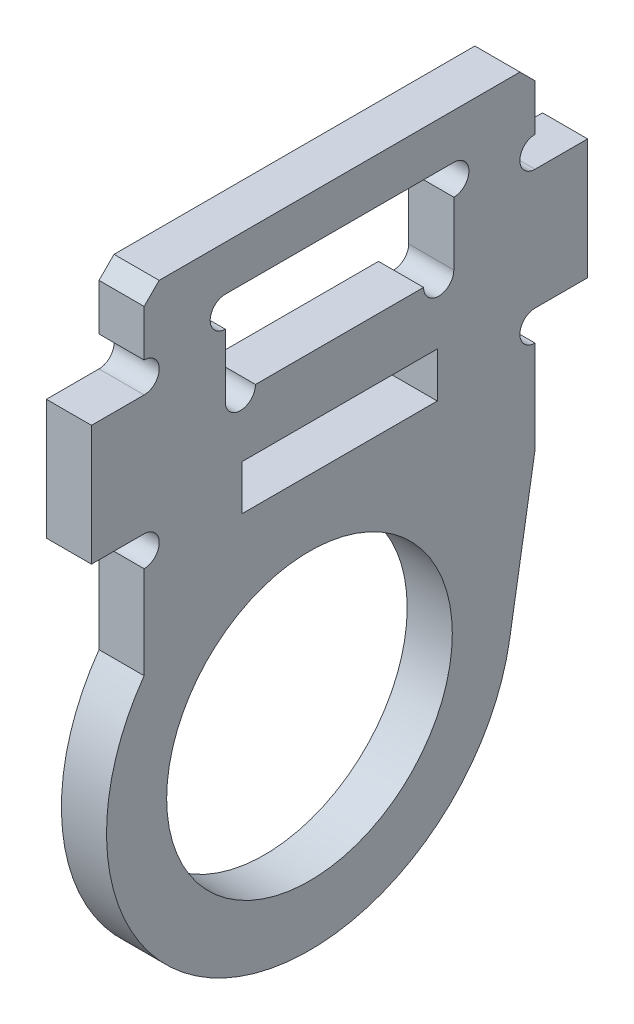
SolidWorks part; units mm, degrees
material "Thornel Mat VMA"
ref_plane "前视基准面" through (0, 0, 0) normal (0, 0, 1) x (1, 0, 0)
ref_plane "上视基准面" through (0, 0, 0) normal (0, 1, 0) x (1, 0, 0)
ref_plane "右视基准面" through (0, 0, 0) normal (1, 0, 0) x (0, 0, -1)
sketch "草图1" plane through (0, 0, 0) normal (1, 0, 0) x (0, 0, -1)
  line L0 (-13, 6.1) -> (13, 6.1)
  line L1 (7.6, -3.1) -> (-7.6, -3.1)
  line L2 (7.6, -3.1) -> (7.6, 3.1)
  line L3 (7.6, 3.1) -> (-7.6, 3.1)
  line L4 (-7.6, -3.1) -> (-7.6, 3.1)
  line L5 (7.6, -3.1) -> (-7.6, 3.1) construction
  line L6 (7.6, 3.1) -> (-7.6, -3.1) construction
  line L7 (13, 6.1) -> (13, 0)
  line L8 (0, 0) -> (0, -16.3564) construction
  line L9 (-13, 6.1) -> (-13, 0)
  line L10 (13, 0) -> (16.5, 0)
  line L11 (16.5, 0) -> (16.5, -8)
  line L12 (16.5, -8) -> (13, -8)
  line L13 (-16.5, -8) -> (-13, -8)
  line L14 (-16.5, 0) -> (-16.5, -8)
  line L15 (-13, 0) -> (-16.5, 0)
  line L16 (-13, -8) -> (-13, -16.1738)
  line L18 (16.5, -4) -> (10.4606, -4) construction
  line L19 (13, -8) -> (13, -16.1738)
  line L20 (6.5, -10.1) -> (-6.5, -10.1)
  line L21 (6.5, -10.1) -> (6.5, -7.1)
  line L22 (6.5, -7.1) -> (-6.5, -7.1)
  line L23 (-6.5, -10.1) -> (-6.5, -7.1)
  line L24 (6.5, -10.1) -> (-6.5, -7.1) construction
  line L25 (6.5, -7.1) -> (-6.5, -10.1) construction
  line L26 (13, -16.1738) -> (11.3143, -26.2315)
  circle A2 centre (6.595, -3.1) radius 1.005
  circle A3 centre (-6.595, -3.1) radius 1.005
  circle A4 centre (-2, -24) radius 9.5
  circle A6 centre (7.6, 2.095) radius 1.005
  circle A7 centre (-7.6, 2.095) radius 1.005
  circle A8 centre (-13, 1.005) radius 1.005
  circle A9 centre (-13, -9.005) radius 1.005
  circle A10 centre (13, -9.005) radius 1.005
  circle A11 centre (13, 1.005) radius 1.005
  arc A12 (-13, -16.1738) -> (11.3143, -26.2315) centre (-2, -24) ccw
  point P0 (0, 0)
  point P40 (0, -8.6)
  dimension "D3" = 19
  dimension "D5" = 2.01
  dimension "D6" = 2
  dimension "D15" = 4
  dimension "D1" = 15.2
  dimension "D2" = 6.2
  dimension "D4" = 24
  dimension "D7" = 26
  dimension "D8" = 3
  dimension "D9" = 3.5
  dimension "D10" = 8
  dimension "D11" = 4
  dimension "D12" = 4
  dimension "D13" = 13
  dimension "D14" = 3
extrude "凸台-拉伸1" add sketch "草图1" along normal blind 3
chamfer "倒角1" distance 1 angle 45 2 edges at (1.5, 6.1, -13) (1.5, 6.1, 13)
